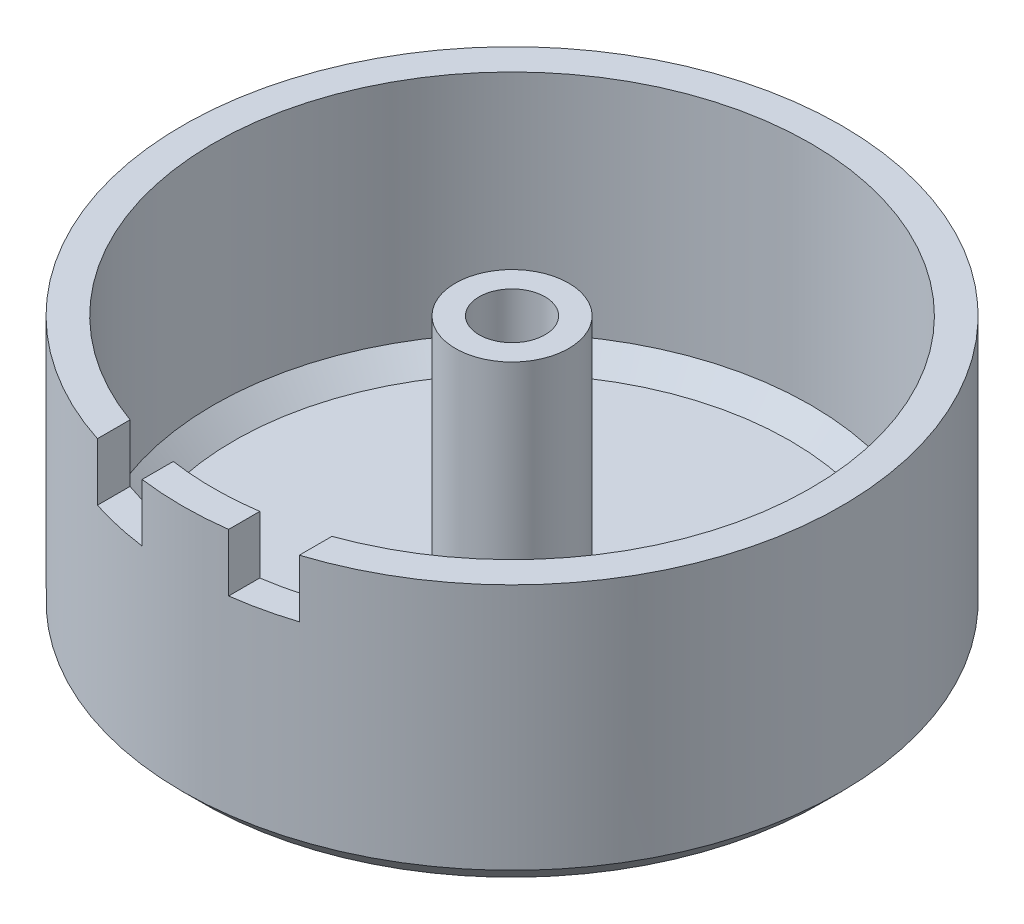
SolidWorks part; units mm, degrees
ref_plane "Front Plane" through (0, 0, 0) normal (0, 0, 1) x (1, 0, 0)
ref_plane "Top Plane" through (0, 0, 0) normal (0, 1, 0) x (1, 0, 0)
ref_plane "Right Plane" through (0, 0, 0) normal (1, 0, 0) x (0, 0, -1)
sketch "Sketch1" plane through (0, 0, 0) normal (0, 0, 1) x (1, 0, 0)
  line L0 (0, 0) -> (0, 7.9248) construction
  line L1 (-14.5, 6.25) -> (-14.5, -4.75)
  line L2 (-13.5, -5.75) -> (-2.75, -5.75)
  line L3 (-2.75, -5.75) -> (-2.75, 6.25)
  line L4 (-2.75, 6.25) -> (-1.6, 6.25)
  line L5 (-1.6, 6.25) -> (-1.6, -6.75)
  line L6 (-1.6, -6.75) -> (-15.003, -6.75)
  line L7 (-15.003, -6.75) -> (-16, -5.753)
  line L8 (-16, -5.753) -> (-16, 6.25)
  line L9 (-16, 6.25) -> (-14.5, 6.25)
  line L10 (-12.5, 4.3498) -> (-12.5, -3.6647) construction
  line L11 (-2.6152, -5.25) -> (9.9772, -5.25) construction
  line L12 (-14.5, -4.75) -> (-13.5, -5.75)
  line L13 (0, 5.25) -> (-11.138, 5.25) construction
  point P3 (-14.5, -5.75)
  point P19 (-1.851, -6.4318)
  point P20 (-1.5853, -6.7385)
  point P21 (0, 0)
  point P22 (0, 0)
  point P24 (0, 0)
  dimension "D1" = 1.6
  dimension "D2" = 2.75
  dimension "D3" = 2
  dimension "D4" = 16
  dimension "D5" = 12.5
  dimension "D6" = 5.25
  dimension "D7" = 1
  dimension "D8" = 135
  dimension "D9" = 1.41
  dimension "D10" = 1
  dimension "D11" = 1
  dimension "D12" = 1
  dimension "D13" = 5.25
  dimension "D14" = 1
revolve "Revolve1" add sketch "Sketch1" angle 360 about L0
sketch "Sketch2" plane through (0, 0, 0) normal (0, 0, 1) x (1, 0, 0)
  line L0 (0, 0) -> (0, 9.3966) construction
  line L1 (-4.9, 6.25) -> (-2.1, 6.25)
  line L2 (-4.9, 6.25) -> (-4.9, 3.45)
  line L3 (-4.9, 3.45) -> (-2.1, 3.45)
  line L4 (-2.1, 6.25) -> (-2.1, 3.45)
  line L5 (4.9, 3.45) -> (2.1, 3.45)
  line L6 (2.1, 6.25) -> (2.1, 3.45)
  line L7 (4.9, 6.25) -> (2.1, 6.25)
  line L8 (4.9, 6.25) -> (4.9, 3.45)
  line L9 (-3.5, 6.25) -> (-3.5, 3.45) construction
  line L10 (3.5, 6.25) -> (3.5, 3.45) construction
  line L11 (14.5, 6.25) -> (-14.5, 6.25) construction
  point P15 (-4.9, 6.25)
  dimension "D1" = 7
  dimension "D2" = 2.8
  dimension "D3" = 2.8
extrude "Cut-Extrude1" cut sketch "Sketch2" along normal blind 10 from offset 10
